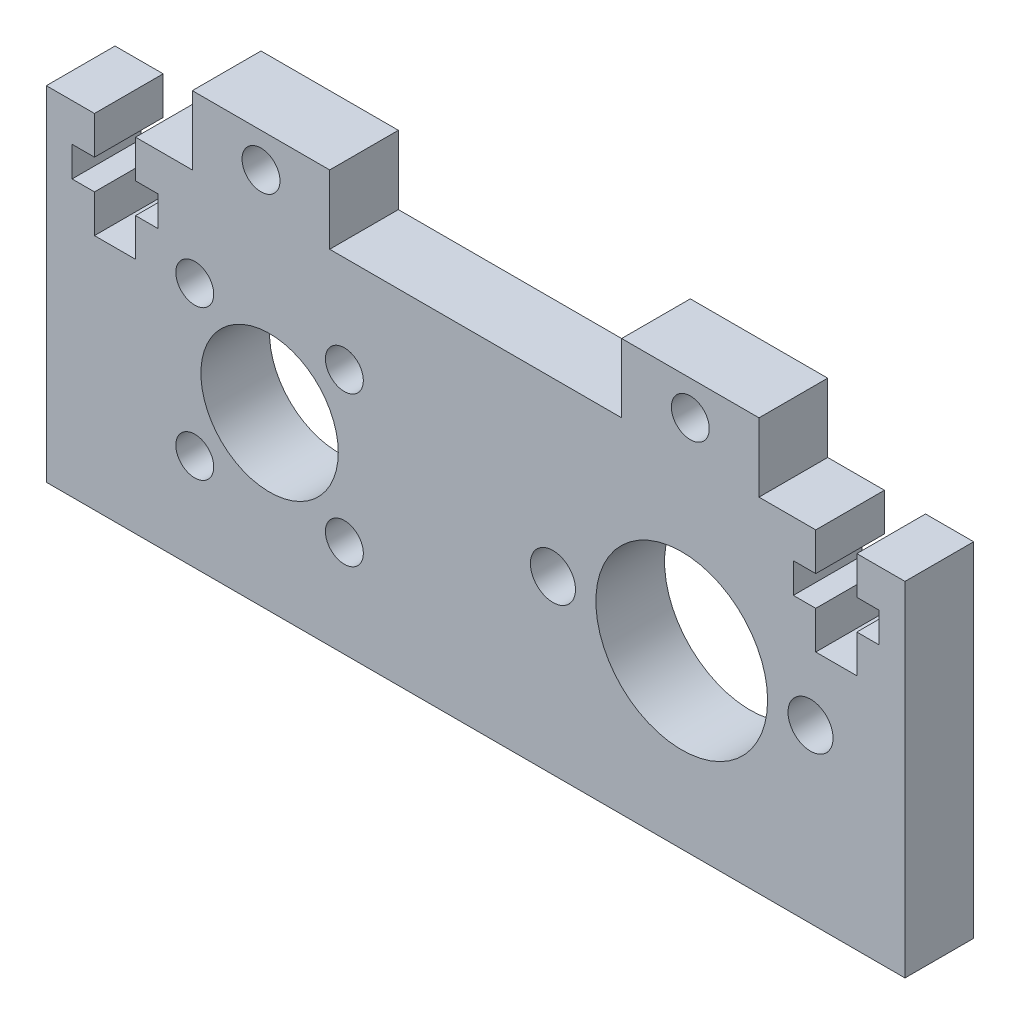
SolidWorks part; units mm, degrees
material "Beech"
ref_plane "Front Plane" through (0, 0, 0) normal (0, 0, 1) x (1, 0, 0)
ref_plane "Top Plane" through (0, 0, 0) normal (0, 1, 0) x (1, 0, 0)
ref_plane "Right Plane" through (0, 0, 0) normal (1, 0, 0) x (0, 0, -1)
sketch "Sketch1" plane through (0, 0, 0) normal (0, 0, 1) x (1, 0, 0)
  line L1 (-39.6875, -15.875) -> (0, -15.875)
  line L2 (-39.6875, -15.875) -> (-39.6875, 15.875)
  line L3 (-39.6875, 15.875) -> (0, 15.875)
  line L4 (0, -15.875) -> (0, 15.875)
  line L5 (-39.6875, -15.875) -> (0, 15.875) construction
  line L6 (-39.6875, 15.875) -> (0, -15.875) construction
  point P0 (-19.8438, 0)
  dimension "D1" = 31.75
  dimension "D2" = 39.6875
extrude "Boss-Extrude1" add sketch "Sketch1" along normal blind 6.35
sketch "Sketch2" plane through (0, 0, 6.35) normal (0, 0, 1) x (1, 0, 0)
  line L1 (-25.9648, -6.9148) -> (-12.1352, -6.9148) construction
  line L2 (-25.9648, -6.9148) -> (-25.9648, 6.9148) construction
  line L3 (-25.9648, 6.9148) -> (-12.1352, 6.9148) construction
  line L4 (-12.1352, -6.9148) -> (-12.1352, 6.9148) construction
  line L5 (-25.9648, -6.9148) -> (-12.1352, 6.9148) construction
  line L6 (-25.9648, 6.9148) -> (-12.1352, -6.9148) construction
  circle A0 centre (-19.05, 0) radius 6.35
  circle A1 centre (-25.9648, 6.9148) radius 1.7526
  circle A2 centre (-12.1352, 6.9148) radius 1.7526
  circle A3 centre (-12.1352, -6.9148) radius 1.7526
  circle A4 centre (-25.9648, -6.9148) radius 1.7526
  dimension "D1" = 12.7
  dimension "D4" = 3.5052
  dimension "D2" = 19.05
  dimension "D3" = 19.558
extrude "Cut-Extrude1" cut sketch "Sketch2" against normal blind 6.35
sketch "Sketch3" plane through (0, 0, 6.35) normal (0, 0, 1) x (1, 0, 0)
  line L0 (-33.3375, 15.875) -> (-33.3375, 6.096) construction
  line L1 (0, 15.875) -> (-39.6875, 15.875) construction
  line L2 (-35.2362, 6.096) -> (-31.4389, 6.096)
  line L3 (-35.2362, 6.096) -> (-35.2362, 9.5964)
  line L4 (-35.2362, 9.5964) -> (-37.3062, 9.5964)
  line L5 (-37.3062, 9.5964) -> (-37.3062, 12.3746)
  line L6 (-37.3062, 12.3746) -> (-35.2362, 12.3746)
  line L7 (-35.2362, 12.3746) -> (-35.2362, 15.875)
  line L8 (-39.6875, 15.875) -> (-39.6875, -15.875) construction
  line L10 (-35.2362, 15.875) -> (-31.4388, 15.875)
  line L11 (-31.4388, 12.3746) -> (-31.4388, 15.875)
  line L12 (-29.3687, 12.3746) -> (-31.4388, 12.3746)
  line L13 (-29.3687, 9.5964) -> (-29.3687, 12.3746)
  line L14 (-31.4388, 9.5964) -> (-29.3687, 9.5964)
  line L15 (-31.4389, 6.096) -> (-31.4388, 9.5964)
  line L16 (-19.8437, 15.875) -> (-19.8438, -15.875) construction
  line L17 (-39.6875, -15.875) -> (0, -15.875) construction
  dimension "D1" = 3.7973
  dimension "D2" = 9.779
  dimension "D3" = 2.7781
  dimension "D4" = 3.9688
  dimension "D5" = 6.35
extrude "Cut-Extrude4" cut sketch "Sketch3" against normal blind 6.35
sketch "Sketch4" plane through (0, 0, 6.35) normal (0, 0, 1) x (1, 0, 0)
  line L1 (-26.1938, 22.225) -> (-13.4938, 22.225)
  line L2 (-26.1938, 22.225) -> (-26.1938, 15.875)
  line L3 (-26.1938, 15.875) -> (-13.4937, 15.875)
  line L4 (-13.4938, 22.225) -> (-13.4937, 15.875)
  line L5 (-26.1938, 22.225) -> (-13.4937, 15.875) construction
  line L6 (-26.1938, 15.875) -> (-13.4938, 22.225) construction
  line L7 (-19.8438, -15.875) -> (-19.8438, 15.875) construction
  line L8 (-39.6875, -15.875) -> (0, -15.875) construction
  line L9 (0, 15.875) -> (-31.4388, 15.875) construction
  circle A0 centre (-19.8438, 19.05) radius 1.7526
  point P0 (-19.8438, 19.05)
  point P5 (-19.8438, 15.875)
  dimension "D3" = 3.5052
  dimension "D1" = 6.35
  dimension "D2" = 12.7
extrude "Boss-Extrude2" add sketch "Sketch4" against normal blind 6.35
mirror "Mirror1" about plane through (0, -15.875, 6.35) normal (-1, 0, 0) of "Cut-Extrude4", "Boss-Extrude1", "Boss-Extrude2"
sketch "Sketch5" plane through (0, 0, 6.35) normal (0, 0, 1) x (1, 0, 0)
  line L0 (7.1438, 0) -> (30.9563, 0) construction
  circle A0 centre (19.05, 0) radius 7.9375
  circle A1 centre (7.1438, 0) radius 2.0828
  circle A2 centre (30.9563, 0) radius 2.0828
  dimension "D1" = 15.875
  dimension "D4" = 4.1656
  dimension "D2" = 19.05
  dimension "D3" = 23.8125
extrude "Cut-Extrude3" cut sketch "Sketch5" against normal blind 6.35
sketch "Sketch6" [suppressed] plane through (0, 0, 6.35) normal (0, 0, 1) x (1, 0, 0)
  circle A0 centre (-19.05, 0) radius 3.048
  dimension "D1" = 6.096
  dimension "D2" = 19.05
extrude "Cut-Extrude5" [suppressed] cut sketch "Sketch6" against normal blind 6.35
ref_plane "Plane1" [suppressed] through (-19.8438, 0, 0) normal (1, 0, 0) x (0, 0, -1)
mirror "Mirror2" [suppressed] about plane through (-19.8438, 0, 0) normal (1, 0, 0)
